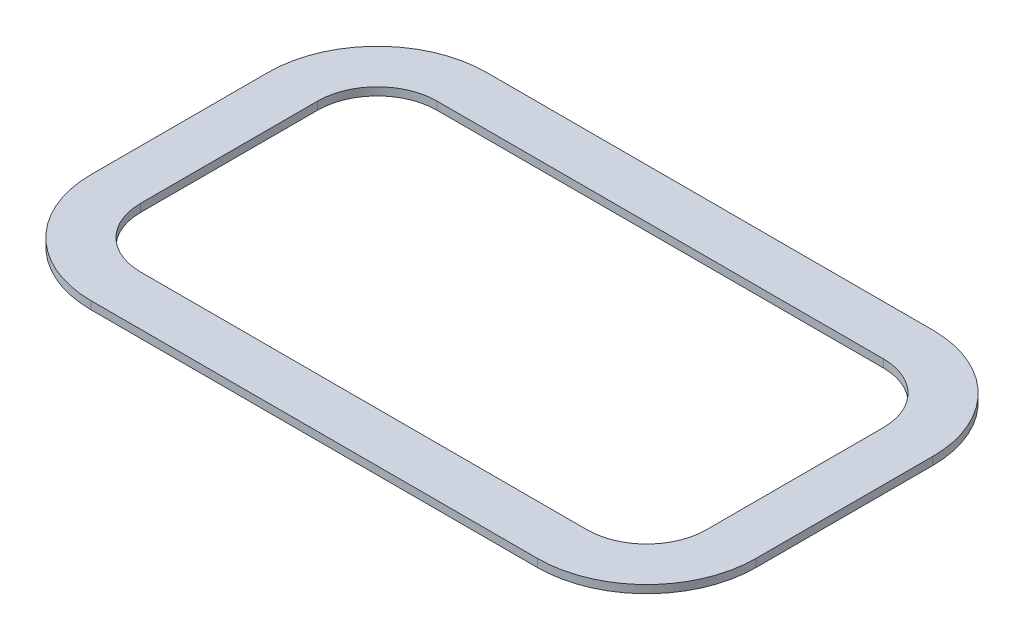
SolidWorks part; units mm, degrees
ref_plane "Front Plane" through (0, 0, 0) normal (0, 0, 1) x (1, 0, 0)
ref_plane "Top Plane" through (0, 0, 0) normal (0, 1, 0) x (1, 0, 0)
ref_plane "Right Plane" through (0, 0, 0) normal (1, 0, 0) x (0, 0, -1)
sketch "Sketch1" plane through (0, 0, 0) normal (0, 1, 0) x (1, 0, 0)
  line L0 (0.8612, 1.5188) -> (225.8912, 1.5188)
  line L1 (0.8612, 26.5188) -> (225.8912, 26.5188)
  line L2 (-54.1388, -28.4812) -> (-54.1388, -117.7412)
  line L3 (0.8612, -172.7412) -> (225.8912, -172.7412)
  line L4 (280.8912, -28.4812) -> (280.8912, -117.7412)
  line L5 (255.8912, -28.4812) -> (255.8912, -117.7412)
  line L6 (0.8612, -147.7412) -> (225.8912, -147.7412)
  line L7 (-29.1388, -28.4812) -> (-29.1388, -117.7412)
  arc A0 (-54.1388, -117.7412) -> (0.8612, -172.7412) centre (0.8612, -117.7412) ccw
  arc A1 (225.8912, -172.7412) -> (280.8912, -117.7412) centre (225.8912, -117.7412) ccw
  arc A2 (225.8912, 26.5188) -> (280.8912, -28.4812) centre (225.8912, -28.4812) cw
  arc A3 (0.8612, 26.5188) -> (-54.1388, -28.4812) centre (0.8612, -28.4812) ccw
  arc A4 (225.8912, 1.5188) -> (255.8912, -28.4812) centre (225.8912, -28.4812) cw
  arc A5 (225.8912, -147.7412) -> (255.8912, -117.7412) centre (225.8912, -117.7412) ccw
  arc A6 (-29.1388, -117.7412) -> (0.8612, -147.7412) centre (0.8612, -117.7412) ccw
  arc A7 (0.8612, 1.5188) -> (-29.1388, -28.4812) centre (0.8612, -28.4812) ccw
  point P6 (-54.1388, -172.7412)
  point P11 (280.8912, 26.5188)
  point P14 (-54.1388, 26.5188)
  dimension "D3" = 55
  dimension "D1" = 335.03
  dimension "D2" = 199.26
  dimension "D4" = 25
extrude "Boss-Extrude1" add sketch "Sketch1" along normal blind 4
